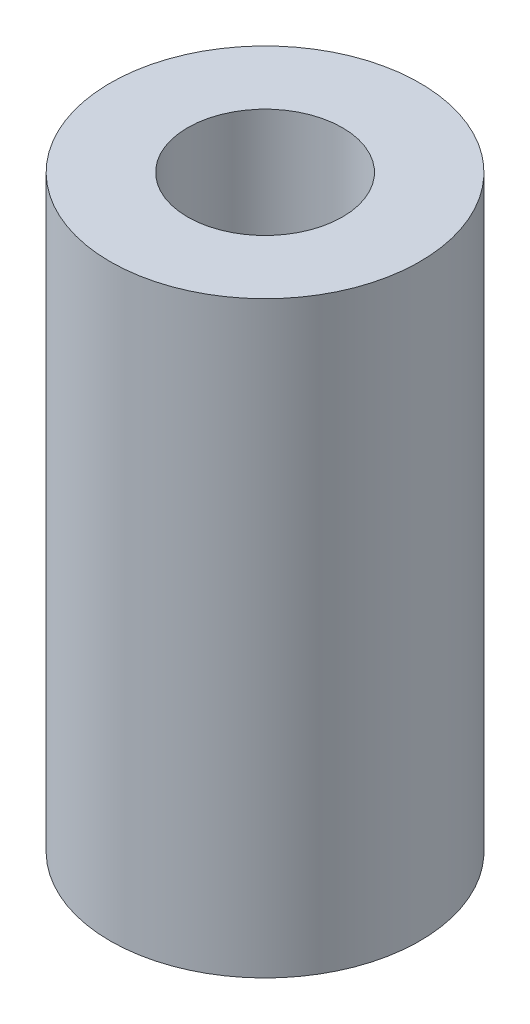
SolidWorks part; units mm, degrees
material "6061 Alloy"
ref_plane "Front Plane" through (0, 0, 0) normal (0, 0, 1) x (1, 0, 0)
ref_plane "Top Plane" through (0, 0, 0) normal (0, 1, 0) x (1, 0, 0)
ref_plane "Right Plane" through (0, 0, 0) normal (1, 0, 0) x (0, 0, -1)
sketch "Sketch1" plane through (0, 0, 0) normal (0, 1, 0) x (1, 0, 0)
  circle A0 centre (0, 0) radius 2.5
  circle A1 centre (0, 0) radius 5
  dimension "D1" = 5
extrude "Boss-Extrude1" add sketch "Sketch1" along normal blind 19
